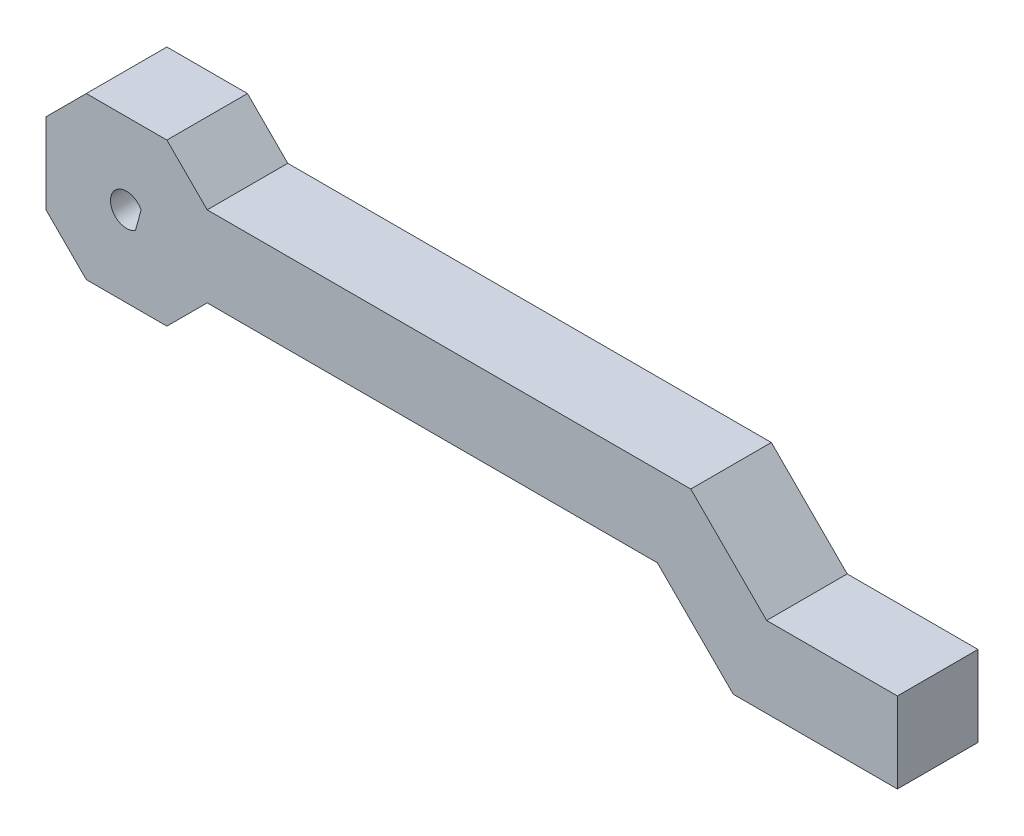
SolidWorks part; units mm, degrees
material "Nylon 6/10"
ref_plane "Front Plane" through (0, 0, 0) normal (0, 0, 1) x (1, 0, 0)
ref_plane "Top Plane" through (0, 0, 0) normal (0, 1, 0) x (1, 0, 0)
ref_plane "Right Plane" through (0, 0, 0) normal (1, 0, 0) x (0, 0, -1)
sketch "Sketch1" plane through (0, 0, 0) normal (0, 0, 1) x (1, 0, 0)
  line L0 (-125.9255, 40.003) -> (-115.9255, 50.003)
  line L1 (-115.9255, 50.003) -> (-95.9255, 50.003)
  line L2 (-125.9255, 40.003) -> (-125.9255, 20.003)
  line L3 (-115.9255, 10.003) -> (-95.9255, 10.003)
  line L9 (-125.9255, 20.003) -> (-115.9255, 10.003)
  line L10 (-95.9255, 10.003) -> (-85.9255, 20.003)
  line L11 (-85.9255, 20.003) -> (25.7902, 20.003)
  line L13 (-95.9255, 50.003) -> (-85.9255, 40.003)
  line L14 (-85.9255, 40.003) -> (34.0745, 40.003)
  line L15 (25.7902, 20.003) -> (44.6204, 1.1728)
  line L16 (44.6204, 1.1728) -> (85.3599, 1.1728)
  line L17 (85.3599, 1.1728) -> (85.3599, 21.1728)
  line L18 (85.3599, 21.1728) -> (52.9047, 21.1728)
  line L19 (52.9047, 21.1728) -> (34.0745, 40.003)
  line L20 (-115.9255, 50.003) -> (-95.9255, 10.003) construction
  line L21 (-95.9255, 50.003) -> (-115.9255, 10.003) construction
  line L22 (-103.7187, 26.6668) -> (-102.3397, 31.7755)
  line L23 (-103.0292, 29.2211) -> (-112.4794, 31.7722) construction
  arc A0 (-102.3397, 31.7755) -> (-103.7187, 26.6668) centre (-105.9255, 30.003) ccw
  point P0 (-125.9255, 50.003)
  point P2 (-125.9255, 10.003)
  point P22 (-109.7873, 31.0455)
  dimension "D12" = 8
  dimension "D1" = 40
  dimension "D2" = 120
  dimension "D3" = 40
  dimension "D6" = 20
  dimension "D7" = 20
  dimension "D8" = 40
  dimension "D9" = 20
  dimension "D10" = 20
  dimension "D11" = 20
  dimension "D13" = 7
extrude "Boss-Extrude1" add sketch "Sketch1" along normal blind 20
